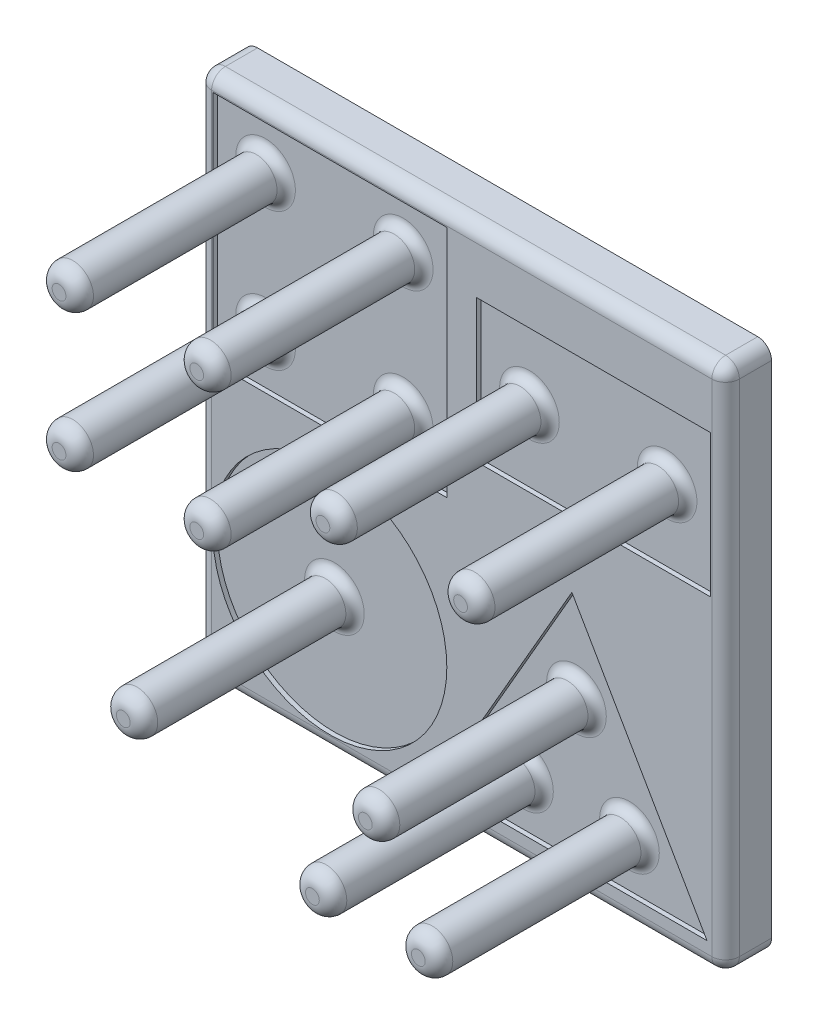
SolidWorks part; units mm, degrees
ref_plane "Front Plane" through (0, 0, 0) normal (0, 0, 1) x (1, 0, 0)
ref_plane "Top Plane" through (0, 0, 0) normal (0, 1, 0) x (1, 0, 0)
ref_plane "Right Plane" through (0, 0, 0) normal (1, 0, 0) x (0, 0, -1)
sketch "Sketch1" plane through (0, 0, 0) normal (0, 0, 1) x (1, 0, 0)
  line L1 (57.5, 57.5) -> (-57.5, 57.5)
  line L2 (57.5, 57.5) -> (57.5, -57.5)
  line L3 (57.5, -57.5) -> (-57.5, -57.5)
  line L4 (-57.5, 57.5) -> (-57.5, -57.5)
  line L5 (57.5, 57.5) -> (-57.5, -57.5) construction
  line L6 (57.5, -57.5) -> (-57.5, 57.5) construction
  point P0 (0, 0)
  dimension "D1" = 115
  dimension "D2" = 115
extrude "Boss-Extrude1" add sketch "Sketch1" along normal blind 10
sketch "Sketch2" plane through (0, 0, 10) normal (0, 0, 1) x (1, 0, 0)
  line L0 (-57.5, 57.5) -> (0, 0) construction
  line L1 (0, 0) -> (-57.5, 0)
  line L2 (0, 0) -> (0, 57.5)
  line L3 (0, 57.5) -> (-57.5, 57.5)
  line L4 (-57.5, 0) -> (-57.5, 57.5)
  line L5 (0, 57.5) -> (-57.5, 0) construction
  line L7 (-3.25, 54.25) -> (-54.25, 54.25)
  line L8 (-3.25, 54.25) -> (-3.25, 3.25)
  line L9 (-3.25, 3.25) -> (-54.25, 3.25)
  line L10 (-54.25, 54.25) -> (-54.25, 3.25)
  line L11 (-3.25, 54.25) -> (-54.25, 3.25) construction
  line L12 (-3.25, 3.25) -> (-54.25, 54.25) construction
  point P6 (-28.75, 28.75)
  dimension "D1" = 57.5
  dimension "D2" = 51
extrude "Cut-Extrude1" cut sketch "Sketch2" against normal blind 1 contours L8 L7 L10 L9
sketch "Sketch3" plane through (0, 0, 9) normal (0, 0, 1) x (1, 0, 0)
  line L0 (-54.25, 54.25) -> (-3.25, 3.25) construction
  line L1 (-3.25, 3.25) -> (-3.25, 54.25)
  line L2 (-3.25, 54.25) -> (-54.25, 3.25) construction
  line L4 (-43.75, 13.75) -> (-13.75, 13.75) construction
  line L5 (-43.75, 13.75) -> (-43.75, 43.75) construction
  line L6 (-43.75, 43.75) -> (-13.75, 43.75) construction
  line L7 (-13.75, 13.75) -> (-13.75, 43.75) construction
  line L8 (-43.75, 13.75) -> (-13.75, 43.75) construction
  line L9 (-43.75, 43.75) -> (-13.75, 13.75) construction
  line L10 (-3.75, 53.75) -> (-53.75, 53.75) construction
  line L11 (-3.75, 53.75) -> (-3.75, 3.75) construction
  line L12 (-3.75, 3.75) -> (-53.75, 3.75) construction
  line L13 (-53.75, 53.75) -> (-53.75, 3.75) construction
  line L14 (-3.75, 53.75) -> (-53.75, 3.75) construction
  line L15 (-3.75, 3.75) -> (-53.75, 53.75) construction
  circle A0 centre (-43.75, 43.75) radius 4.5
  circle A1 centre (-13.75, 43.75) radius 4.5
  circle A2 centre (-13.75, 13.75) radius 4.5
  circle A3 centre (-43.75, 13.75) radius 4.5
  circle A4 centre (-43.75, 43.75) radius 5 construction
  circle A5 centre (-13.75, 43.75) radius 5 construction
  circle A6 centre (-13.75, 13.75) radius 5 construction
  circle A7 centre (-43.75, 13.75) radius 5 construction
  point P4 (-28.75, 28.75)
  point P21 (-28.75, 28.75)
  dimension "D2" = 9
  dimension "D3" = 9
  dimension "D4" = 9
  dimension "D5" = 9
  dimension "D6" = 10
  dimension "D7" = 10
  dimension "D8" = 10
  dimension "D9" = 10
  dimension "D1" = 30
  dimension "D10" = 50
extrude "Boss-Extrude2" add sketch "Sketch3" along normal blind 45 contours A0 | A1 | A2 | A3
fillet "Fillet1" radius 2 4 edges at (-39.25, 13.75, 9) (-9.25, 13.75, 9) (-9.25, 43.75, 9) (-39.25, 43.75, 9)
fillet "Fillet2" radius 3 4 edges at (-39.25, 13.75, 54) (-9.25, 13.75, 54) (-9.25, 43.75, 54) (-39.25, 43.75, 54)
sketch "Sketch4" plane through (0, 0, 10) normal (0, 0, 1) x (1, 0, 0)
  line L0 (0, 57.5) -> (57.5, 0) construction
  line L1 (0, 0) -> (57.5, 0) construction
  line L2 (0, 0) -> (0, 57.5) construction
  line L3 (0, 57.5) -> (57.5, 57.5) construction
  line L4 (57.5, 0) -> (57.5, 57.5) construction
  line L5 (57.5, 0) -> (0, 0)
  line L6 (0, 0) -> (57.5, 57.5) construction
  line L8 (54.25, 13.25) -> (3.25, 13.25)
  line L9 (54.25, 13.25) -> (54.25, 44.25)
  line L10 (54.25, 44.25) -> (3.25, 44.25)
  line L11 (3.25, 13.25) -> (3.25, 44.25)
  line L12 (54.25, 13.25) -> (3.25, 44.25) construction
  line L13 (54.25, 44.25) -> (3.25, 13.25) construction
  point P6 (28.75, 28.75)
  dimension "D1" = 51
  dimension "D2" = 31
extrude "Cut-Extrude2" cut sketch "Sketch4" against normal blind 1 contours L11 L8 L9 L10
sketch "Sketch5" plane through (0, 0, 9) normal (0, 0, 1) x (1, 0, 0)
  line L0 (3.25, 44.25) -> (54.25, 13.25) construction
  line L1 (54.25, 13.25) -> (54.25, 44.25)
  line L2 (54.25, 44.25) -> (3.25, 13.25) construction
  line L3 (-0.6858, 28.75) -> (59.8973, 28.75) construction
  line L4 (53.75, 13.5539) -> (3.75, 13.5539) construction
  line L5 (53.75, 13.5539) -> (53.75, 43.9461) construction
  line L6 (53.75, 43.9461) -> (3.75, 43.9461) construction
  line L7 (3.75, 13.5539) -> (3.75, 43.9461) construction
  line L8 (53.75, 13.5539) -> (3.75, 43.9461) construction
  line L9 (53.75, 43.9461) -> (3.75, 13.5539) construction
  circle A0 centre (13.75, 28.75) radius 4.5
  circle A1 centre (43.75, 28.75) radius 4.5
  circle A2 centre (13.75, 28.75) radius 5 construction
  circle A3 centre (43.75, 28.75) radius 5 construction
  point P4 (28.75, 28.75)
  dimension "D3" = 9
  dimension "D4" = 9
  dimension "D7" = 10
  dimension "D8" = 10
  dimension "D1" = 50
  dimension "D2" = 30.3922
  dimension "D5" = 15
  dimension "D6" = 15
extrude "Boss-Extrude3" add sketch "Sketch5" along normal blind 45 contours A0 | A1
fillet "Fillet3" radius 3 2 edges at (48.25, 28.75, 54) (18.25, 28.75, 54)
fillet "Fillet4" radius 2 2 edges at (48.25, 28.75, 9) (18.25, 28.75, 9)
sketch "Sketch11" plane through (0, 0, 10) normal (0, 0, 1) x (1, 0, 0)
  line L0 (-57.5, 0) -> (0, -57.5) construction
  line L1 (0, 0) -> (-57.5, 0) construction
  line L2 (0, 0) -> (0, -57.5) construction
  line L3 (0, -57.5) -> (-57.5, -57.5) construction
  line L4 (-57.5, 0) -> (-57.5, -57.5) construction
  line L5 (0, -57.5) -> (0, 0)
  line L6 (0, 0) -> (-57.5, -57.5) construction
  circle A0 centre (-28.75, -28.75) radius 5 construction
  circle A1 centre (-28.75, -28.75) radius 4.5
  circle A2 centre (-28.75, -28.75) radius 25.5
  dimension "D1" = 9
  dimension "D2" = 10
  dimension "D3" = 51
extrude "Cut-Extrude5" cut sketch "Sketch11" against normal blind 1 contours A2 A1
sketch "Sketch14" plane through (0, 0, 10) normal (0, 0, 1) x (1, 0, 0)
  circle A0 centre (-28.75, -28.75) radius 4.5
extrude "Boss-Extrude5" add sketch "Sketch14" along normal blind 45
fillet "Fillet7" radius 3 1 edges at (-24.25, -28.75, 55)
fillet "Fillet8" radius 2 1 edges at (-24.25, -28.75, 9)
sketch "Sketch6" plane through (0, 0, 10) normal (0, 0, 1) x (1, 0, 0)
  line L0 (24, -35) -> (24, -1) construction
  line L1 (0, 0) -> (57.5, 0) construction
  line L2 (0, 0) -> (0, -57.5) construction
  line L3 (0, -57.5) -> (57.5, -57.5) construction
  line L4 (57.5, 0) -> (57.5, -57.5) construction
  line L5 (24, -1) -> (-5.4449, -52)
  line L6 (-5.4449, -52) -> (53.4449, -52)
  line L7 (53.4449, -52) -> (24, -1)
  line L8 (24, -21.6667) -> (12.453, -41.6667) construction
  line L9 (12.453, -41.6667) -> (35.547, -41.6667) construction
  line L10 (35.547, -41.6667) -> (24, -21.6667) construction
  circle A0 centre (24, -35) radius 17 construction
  circle A1 centre (24, -35) radius 6.6667 construction
  circle A2 centre (24, -21.6667) radius 4.5
  circle A3 centre (35.547, -41.6667) radius 4.5
  circle A4 centre (12.453, -41.6667) radius 4.5
  circle A5 centre (24, -21.6667) radius 5 construction
  circle A6 centre (35.547, -41.6667) radius 5 construction
  circle A7 centre (12.453, -41.6667) radius 5 construction
  dimension "D5" = 9
  dimension "D6" = 9
  dimension "D7" = 9
  dimension "D8" = 10
  dimension "D9" = 10
  dimension "D10" = 10
  dimension "D1" = 51
  dimension "D2" = 35
  dimension "D3" = 24
  dimension "D4" = 20
extrude "Cut-Extrude6" cut sketch "Sketch6" against normal blind 1 contours L5 L6 L7 | A2 | A3 | A4
sketch "Sketch16" plane through (0, 0, 10) normal (0, 0, 1) x (1, 0, 0)
  circle A0 centre (24, -21.6667) radius 4.5
  circle A1 centre (12.453, -41.6667) radius 4.5
  circle A2 centre (35.547, -41.6667) radius 4.5
  dimension "D1" = 9
  dimension "D2" = 9
  dimension "D3" = 9
extrude "Boss-Extrude6" add sketch "Sketch16" along normal blind 45
fillet "Fillet9" radius 2 3 edges at (16.953, -41.6667, 9) (40.047, -41.6667, 9) (28.5, -21.6667, 9)
fillet "Fillet10" radius 3 3 edges at (40.047, -41.6667, 55) (16.953, -41.6667, 55) (28.5, -21.6667, 55)
fillet "Fillet11" radius 3 8 edges at (57.5, 57.5, 5) (57.5, 0, 10) (0, 57.5, 10) (-57.5, 57.5, 5) (-57.5, 0, 10) (0, -57.5, 10) (-57.5, -57.5, 5) (57.5, -57.5, 5)
sketch "Sketch17" plane through (0, 0, 0) normal (0, 0, 1) x (1, 0, 0)
  line L1 (-57.75, 57.75) -> (57.75, 57.75) construction
  line L2 (-57.75, 57.75) -> (-57.75, -57.75) construction
  line L3 (-57.75, -57.75) -> (57.75, -57.75) construction
  line L4 (57.75, 57.75) -> (57.75, -57.75) construction
  line L5 (-57.75, 57.75) -> (57.75, -57.75) construction
  line L6 (-57.75, -57.75) -> (57.75, 57.75) construction
  point P0 (0, 0)
  dimension "D1" = 115.5
  dimension "D2" = 115.5
